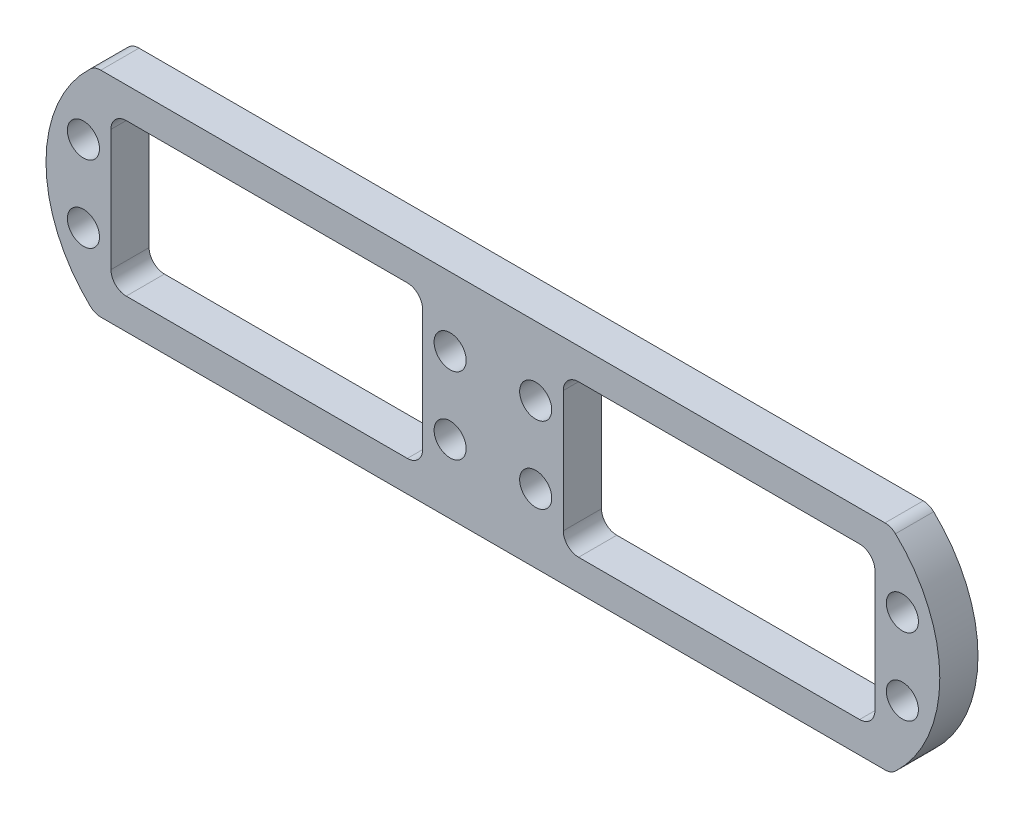
SolidWorks part; units mm, degrees
material "Alliage 1060"
ref_plane "Plan de face" through (0, 0, 0) normal (0, 0, 1) x (1, 0, 0)
ref_plane "Plan de dessus" through (0, 0, 0) normal (0, 1, 0) x (1, 0, 0)
ref_plane "Plan de droite" through (0, 0, 0) normal (1, 0, 0) x (0, 0, -1)
sketch "Esquisse1" plane through (0, 0, 0) normal (0, 0, 1) x (1, 0, 0)
  line L0 (-11.3248, 14) -> (91.3248, 14)
  line L1 (91.3248, -14) -> (-11.3248, -14)
  line L2 (88, 9.95) -> (51.2, 9.95) construction
  line L3 (0, 0) -> (80, 0) construction
  line L4 (51.2154, 9.95) -> (88, 9.95)
  line L5 (49.2154, 7.95) -> (49.2154, -7.95)
  line L6 (51.2154, -9.95) -> (88, -9.95)
  line L7 (90, 7.95) -> (90, -7.95)
  line L8 (90, -7.95) -> (90, 7.95) construction
  line L9 (49.2154, -7.95) -> (49.2154, 7.95) construction
  line L10 (51.2, -9.95) -> (88, -9.95) construction
  line L11 (30.8, -7.95) -> (30.8, 7.95) construction
  line L12 (-8, 9.95) -> (28.8, 9.95)
  line L13 (-10, 7.95) -> (-10, -7.95)
  line L14 (-8, -9.95) -> (28.8, -9.95)
  line L15 (30.8, 7.95) -> (30.8, -7.95)
  line L16 (-8, -9.95) -> (28.8, -9.95) construction
  line L17 (-10, 7.95) -> (-10, -7.95) construction
  line L18 (28.8, 9.95) -> (-8, 9.95) construction
  arc A0 (92.6974, 13.4545) -> (92.6974, -13.4545) centre (80, 0) cw
  arc A1 (-12.6974, -13.4545) -> (-12.6974, 13.4545) centre (0, 0) cw
  circle A2 centre (80, 0) radius 6.15 construction
  circle A3 centre (0, 0) radius 6.45 construction
  arc A4 (92.6974, -13.4545) -> (91.3248, -14) centre (91.3248, -12) cw
  arc A5 (91.3248, 14) -> (92.6974, 13.4545) centre (91.3248, 12) cw
  arc A6 (49.2154, -7.95) -> (51.2154, -9.95) centre (51.2154, -7.95) ccw
  arc A7 (51.2154, 9.95) -> (49.2154, 7.95) centre (51.2154, 7.95) ccw
  arc A8 (88, 9.95) -> (90, 7.95) centre (88, 7.95) cw
  arc A9 (88, -9.95) -> (90, -7.95) centre (88, -7.95) ccw
  arc A10 (-11.3248, -14) -> (-12.6974, -13.4545) centre (-11.3248, -12) cw
  arc A11 (-11.3248, 14) -> (-12.6974, 13.4545) centre (-11.3248, 12) ccw
  arc A12 (-8, 9.95) -> (-10, 7.95) centre (-8, 7.95) ccw
  arc A13 (-10, -7.95) -> (-8, -9.95) centre (-8, -7.95) ccw
  arc A14 (28.8, -9.95) -> (30.8, -7.95) centre (28.8, -7.95) ccw
  arc A15 (28.8, 9.95) -> (30.8, 7.95) centre (28.8, 7.95) cw
  dimension "D3" = 18.5
  dimension "D2" = 2
  dimension "D1" = 28
extrude "Extrusion1" add sketch "Esquisse1" along normal blind 5
sketch "Esquisse2" plane through (0, 0, 0) normal (0, 0, 1) x (1, 0, 0)
  circle A0 centre (-13.6, 5) radius 2.1
  circle A1 centre (45.6, -5) radius 2.1
  circle A2 centre (34.4, 5) radius 2.1
  circle A3 centre (-13.6, -5) radius 2.1
  circle A4 centre (93.6, 5) radius 2.1
  circle A5 centre (93.6, -5) radius 2.1
  circle A6 centre (45.6, 5) radius 2.1
  circle A7 centre (34.4, -5) radius 2.1
  arc A8 (-14.9151, 3.4932) -> (-14.9151, 6.5068) centre (-13.6, 5) ccw construction
  arc A9 (-14.9151, -6.5068) -> (-14.9151, -3.4932) centre (-13.6, -5) ccw construction
  arc A10 (44.2849, 3.4932) -> (44.2849, 6.5068) centre (45.6, 5) ccw construction
  arc A11 (35.9123, 6.7329) -> (35.9123, 3.2671) centre (34.4, 5) ccw construction
  arc A12 (44.0877, -6.7329) -> (44.0877, -3.2671) centre (45.6, -5) ccw construction
  arc A13 (35.9123, -3.2671) -> (35.9123, -6.7329) centre (34.4, -5) ccw construction
  arc A14 (95.1123, -3.2671) -> (95.1123, -6.7329) centre (93.6, -5) ccw construction
  arc A15 (95.1123, 6.7329) -> (95.1123, 3.2671) centre (93.6, 5) ccw construction
  dimension "D1" = 4.2
extrude "Enlèv. mat.-Extru.1" cut sketch "Esquisse2" along normal through all
